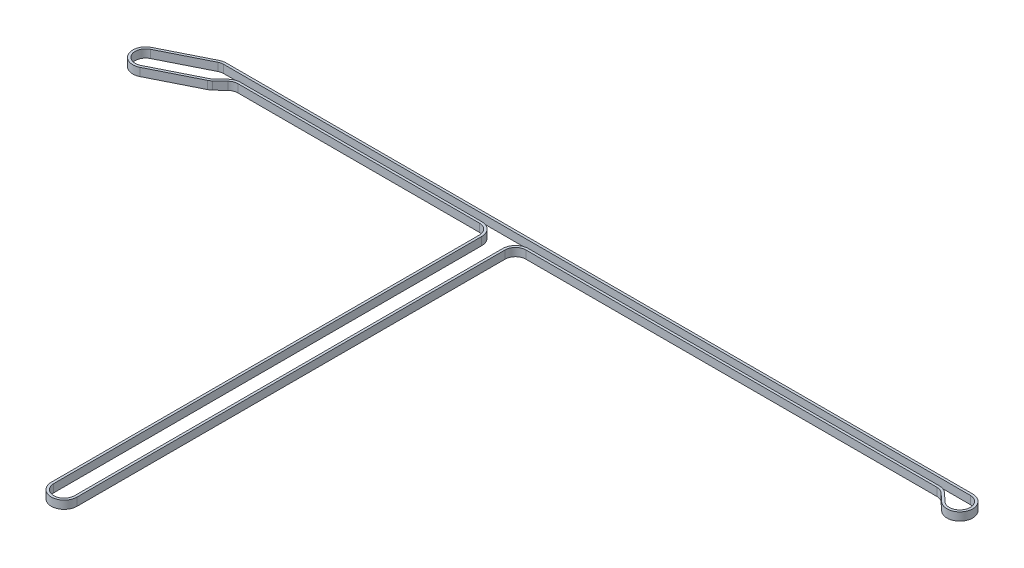
SolidWorks part; units mm, degrees
material "Silicon Rubber"
ref_plane "Front Plane" through (0, 0, 0) normal (0, 0, 1) x (1, 0, 0)
ref_plane "Top Plane" through (0, 0, 0) normal (0, 1, 0) x (1, 0, 0)
ref_plane "Right Plane" through (0, 0, 0) normal (1, 0, 0) x (0, 0, -1)
sketch "Sketch1" plane through (0, 0, 0) normal (0, 1, 0) x (1, 0, 0)
  line L0 (192.8324, 8) -> (221.8324, 8) construction
  line L1 (192.8324, 8) -> (42.8324, 8) construction
  line L2 (492, 14) -> (28, 14) construction
  circle A0 centre (0, 0) radius 6.38
  circle A1 centre (28, 14) radius 6.5
  circle A2 centre (42.8324, 8) radius 6.5
  circle A3 centre (192.8324, 8) radius 6.5
  circle A4 centre (221.8324, 8) radius 6.5
  circle A5 centre (477.1676, 8) radius 6.5
  circle A6 centre (492, 14) radius 6.5
  circle A7 centre (207.3324, -258) radius 6.5
  dimension "D1" = 12.76
  dimension "D3" = 28
  dimension "D4" = 13
  dimension "D6" = 6
  dimension "D8" = 150
  dimension "D12" = 266
  dimension "D13" = 14.5
  dimension "D2" = 14
  dimension "D5" = 16
  dimension "D7" = 29
  dimension "D9" = 464
  dimension "D10" = 16
  dimension "D11" = 6
sketch "Sketch2" plane through (0, 0, 0) normal (0, 1, 0) x (1, 0, 0)
  line L0 (3.5777, -7.1554) -> (31.5777, 6.8446)
  line L1 (33.4527, 8.1461) -> (38.4021, 12.7563)
  line L2 (42.8324, 14.5) -> (192.8324, 14.5)
  line L3 (199.3324, 8) -> (199.3324, -258)
  line L4 (215.3324, -258) -> (215.3324, 8)
  line L5 (192.8324, 8) -> (221.8324, 8) construction
  line L6 (221.8324, 14.5) -> (477.1676, 14.5)
  line L7 (-3.5777, 7.1554) -> (24.4223, 21.1554)
  line L8 (28, 22) -> (492, 22)
  line L9 (486.5473, 8.1461) -> (481.5979, 12.7563)
  line L10 (2.9069, -5.8138) -> (30.9069, 8.1862)
  line L11 (32.4303, 9.2437) -> (37.3797, 13.8539)
  line L12 (42.8324, 16) -> (192.8324, 16)
  line L13 (200.8324, 8) -> (200.8324, -258)
  line L14 (213.8324, -258) -> (213.8324, 8)
  line L15 (221.8324, 16) -> (477.1676, 16)
  line L16 (487.5697, 9.2437) -> (482.6203, 13.8539)
  line L17 (28, 20.5) -> (492, 20.5)
  line L18 (-2.9069, 5.8138) -> (25.0931, 19.8138)
  circle A0 centre (492, 14) radius 6.5 construction
  arc A1 (30.9069, 8.1862) -> (32.4303, 9.2437) centre (28, 14) ccw
  arc A2 (31.5777, 6.8446) -> (33.4527, 8.1461) centre (28, 14) ccw
  circle A3 centre (42.8324, 8) radius 6.5 construction
  arc A4 (38.4021, 12.7563) -> (42.8324, 14.5) centre (42.8324, 8) cw
  circle A5 centre (192.8324, 8) radius 6.5 construction
  arc A6 (192.8324, 14.5) -> (199.3324, 8) centre (192.8324, 8) cw
  arc A7 (199.3324, -258) -> (215.3324, -258) centre (207.3324, -258) ccw
  circle A8 centre (221.8324, 8) radius 6.5 construction
  arc A9 (215.3324, 8) -> (221.8324, 14.5) centre (221.8324, 8) cw
  circle A10 centre (477.1676, 8) radius 6.5 construction
  circle A11 centre (28, 14) radius 6.5 construction
  arc A12 (3.5777, -7.1554) -> (-3.5777, 7.1554) centre (0, 0) cw
  circle A13 centre (0, 0) radius 6.38 construction
  arc A14 (24.4223, 21.1554) -> (28, 22) centre (28, 14) cw
  arc A15 (492, 22) -> (486.5473, 8.1461) centre (492, 14) cw
  arc A16 (481.5979, 12.7563) -> (477.1676, 14.5) centre (477.1676, 8) ccw
  arc A18 (37.3797, 13.8539) -> (42.8324, 16) centre (42.8324, 8) cw
  arc A19 (192.8324, 16) -> (200.8324, 8) centre (192.8324, 8) cw
  arc A20 (200.8324, -258) -> (213.8324, -258) centre (207.3324, -258) ccw
  arc A21 (213.8324, 8) -> (221.8324, 16) centre (221.8324, 8) cw
  arc A22 (482.6203, 13.8539) -> (477.1676, 16) centre (477.1676, 8) ccw
  arc A23 (492, 20.5) -> (487.5697, 9.2437) centre (492, 14) cw
  arc A24 (25.0931, 19.8138) -> (28, 20.5) centre (28, 14) cw
  arc A25 (2.9069, -5.8138) -> (-2.9069, 5.8138) centre (0, 0) cw
  dimension "D1" = 1.5
extrude "Boss-Extrude1" add sketch "Sketch2" along normal blind 5
